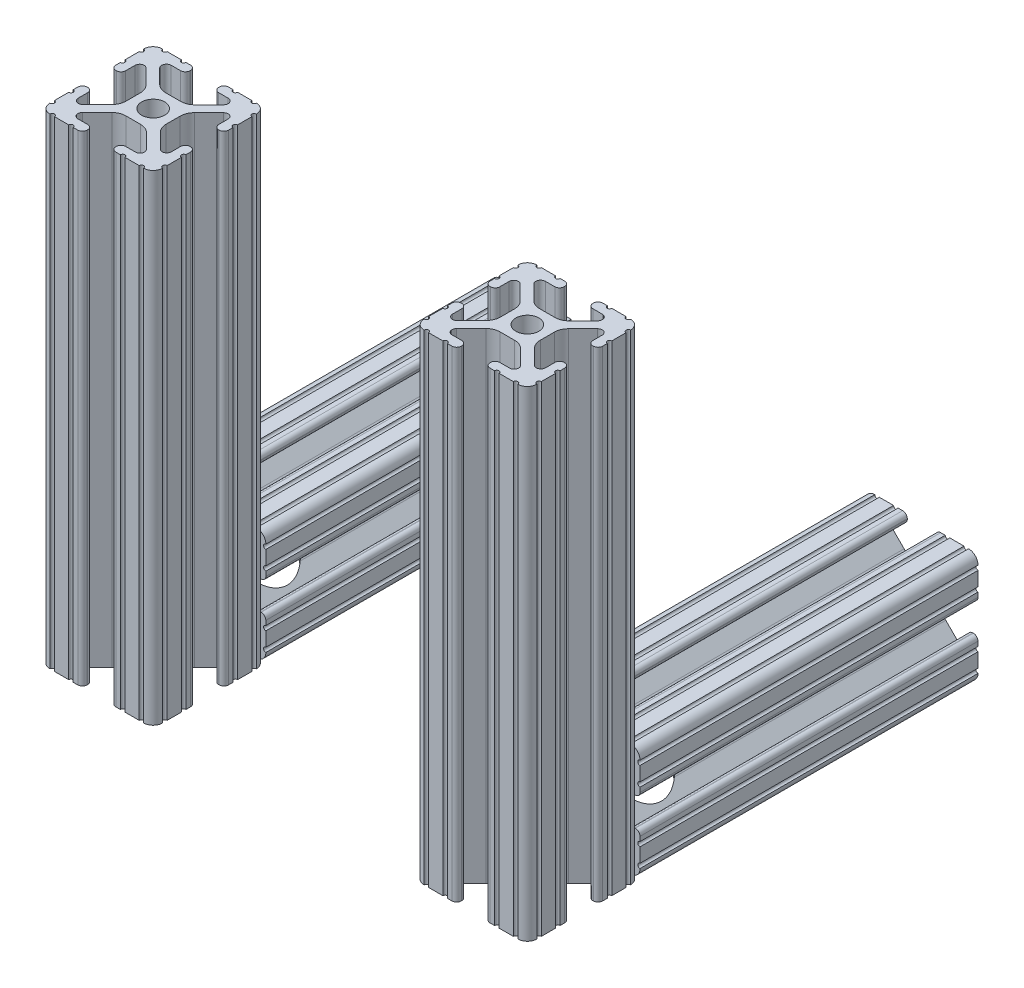
SolidWorks part; units mm, degrees
material "6061-T6 (SS)"
ref_plane "Front" through (0, 0, 0) normal (0, 0, 1) x (1, 0, 0)
ref_plane "Top" through (0, 0, 0) normal (0, 1, 0) x (1, 0, 0)
ref_plane "Right" through (0, 0, 0) normal (1, 0, 0) x (0, 0, -1)
sketch "Sketch1" plane through (0, 0, 0) normal (0, 0, 1) x (1, 0, 0)
  line L0 (0, -54.1622) -> (0, 54.1622)
  line L1 (42.1775, 54.1622) -> (42.1775, -54.1622)
  line L2 (-42.1775, 54.1622) -> (-42.1775, -54.1622)
  line L3 (-42.1775, 54.1622) -> (0, 54.1622) construction
  line L4 (0, 54.1622) -> (42.1775, 54.1622) construction
  line L5 (-42.1775, -54.1622) -> (0, -54.1622) construction
  line L6 (0, -54.1622) -> (42.1775, -54.1622) construction
  dimension "D1" = 108.3245
  dimension "D2" = 42.1775
other "10 1010 PROFILE(1)"
ref_plane "Plane1" through (-42.1775, 54.1622, 0) normal (0, -1, 0) x (1, 0, 0)
sketch "Sketch110" plane through (-42.1775, 54.1622, 0) normal (0, -1, 0) x (1, 0, 0)
  line L1 (12.7, 12.7) -> (-12.7, 12.7) construction
  line L2 (12.7, 12.7) -> (12.7, -12.7) construction
  line L3 (12.7, -12.7) -> (-12.7, -12.7) construction
  line L4 (-12.7, 12.7) -> (-12.7, -12.7) construction
  line L5 (12.7, 12.7) -> (-12.7, -12.7) construction
  line L6 (12.7, -12.7) -> (-12.7, 12.7) construction
  line L88 (-1.7093, -4.4958) -> (1.7093, -4.4958)
  line L89 (3.9523, -5.4237) -> (7.1797, -8.6452)
  line L90 (6.4164, -10.4902) -> (4.2875, -10.4902)
  line L91 (3.2385, -11.5392) -> (3.2385, -11.651)
  line L92 (4.2875, -12.7) -> (5.3171, -12.7)
  line L93 (6.3331, -12.7) -> (9.5504, -12.7)
  line L94 (12.7, -9.5504) -> (12.7, -6.3331)
  line L95 (12.7, -5.3171) -> (12.7, -4.2875)
  line L96 (11.651, -3.2385) -> (11.5392, -3.2385)
  line L97 (10.4902, -4.2875) -> (10.4902, -6.4021)
  line L98 (8.737, -7.1292) -> (5.4405, -3.8388)
  line L99 (4.5085, -1.5917) -> (4.5085, 1.5917)
  line L100 (5.4405, 3.8388) -> (8.737, 7.1292)
  line L101 (10.4902, 6.4021) -> (10.4902, 4.2875)
  line L102 (11.5392, 3.2385) -> (11.651, 3.2385)
  line L103 (12.7, 4.2875) -> (12.7, 5.3171)
  line L104 (12.7, 6.3331) -> (12.7, 9.5504)
  line L105 (9.5504, 12.7) -> (6.3331, 12.7)
  line L106 (5.3171, 12.7) -> (4.2875, 12.7)
  line L107 (3.2384, 11.651) -> (3.2384, 11.5392)
  line L108 (4.2875, 10.4902) -> (6.4768, 10.4902)
  line L109 (7.2072, 8.7245) -> (3.9003, 5.4237)
  line L110 (1.6573, 4.4958) -> (-1.6573, 4.4958)
  line L111 (-3.9003, 5.4237) -> (-7.2072, 8.7245)
  line L112 (-6.4768, 10.4902) -> (-4.2875, 10.4902)
  line L113 (-3.2384, 11.5392) -> (-3.2384, 11.651)
  line L114 (-4.2875, 12.7) -> (-5.3171, 12.7)
  line L115 (-6.3331, 12.7) -> (-9.5504, 12.7)
  line L116 (-12.7, 9.5504) -> (-12.7, 6.3331)
  line L117 (-12.7, 5.3171) -> (-12.7, 4.2875)
  line L118 (-11.651, 3.2385) -> (-11.5392, 3.2385)
  line L119 (-10.4902, 4.2875) -> (-10.4902, 6.4021)
  line L120 (-8.737, 7.1292) -> (-5.4405, 3.8388)
  line L121 (-4.5085, 1.5917) -> (-4.5085, -1.5917)
  line L122 (-5.4405, -3.8388) -> (-8.737, -7.1292)
  line L123 (-10.4902, -6.4021) -> (-10.4902, -4.2875)
  line L124 (-11.5392, -3.2385) -> (-11.651, -3.2385)
  line L125 (-12.7, -4.2875) -> (-12.7, -5.3171)
  line L126 (-12.7, -6.3331) -> (-12.7, -9.5504)
  line L127 (-9.5504, -12.7) -> (-6.3331, -12.7)
  line L128 (-5.3171, -12.7) -> (-4.2875, -12.7)
  line L129 (-3.2385, -11.651) -> (-3.2385, -11.5392)
  line L130 (-4.2875, -10.4902) -> (-6.4164, -10.4902)
  line L131 (-7.1797, -8.6452) -> (-3.9523, -5.4237)
  circle A1 centre (0, 0) radius 2.6035
  arc A104 (-1.7093, -4.4958) -> (-3.9523, -5.4237) centre (-1.7093, -7.6708) ccw
  arc A105 (3.9523, -5.4237) -> (1.7093, -4.4958) centre (1.7093, -7.6708) ccw
  arc A106 (6.4164, -10.4902) -> (7.1797, -8.6452) centre (6.4164, -9.4098) ccw
  arc A107 (4.2875, -10.4902) -> (3.2385, -11.5392) centre (4.2875, -11.5392) ccw
  arc A108 (3.2385, -11.651) -> (4.2875, -12.7) centre (4.2875, -11.651) ccw
  arc A109 (6.3331, -12.7) -> (5.3171, -12.7) centre (5.8251, -12.7) ccw
  arc A110 (10.5664, -12.6998) -> (9.5504, -12.7) centre (10.0584, -12.7) ccw
  arc A111 (10.5664, -12.6998) -> (12.6998, -10.5664) centre (10.5918, -10.5918) ccw
  arc A112 (12.7, -9.5504) -> (12.6998, -10.5664) centre (12.7, -10.0584) ccw
  arc A113 (12.7, -5.3171) -> (12.7, -6.3331) centre (12.7, -5.8251) ccw
  arc A114 (12.7, -4.2875) -> (11.651, -3.2385) centre (11.651, -4.2875) ccw
  arc A115 (11.5392, -3.2385) -> (10.4902, -4.2875) centre (11.5392, -4.2875) ccw
  arc A116 (8.737, -7.1292) -> (10.4902, -6.4021) centre (9.4628, -6.4021) ccw
  arc A117 (4.5085, -1.5917) -> (5.4405, -3.8388) centre (7.6835, -1.5917) ccw
  arc A118 (5.4405, 3.8388) -> (4.5085, 1.5917) centre (7.6835, 1.5917) ccw
  arc A119 (10.4902, 6.4021) -> (8.737, 7.1292) centre (9.4628, 6.4021) ccw
  arc A120 (10.4902, 4.2875) -> (11.5392, 3.2385) centre (11.5392, 4.2875) ccw
  arc A121 (11.651, 3.2385) -> (12.7, 4.2875) centre (11.651, 4.2875) ccw
  arc A122 (12.7, 6.3331) -> (12.7, 5.3171) centre (12.7, 5.8251) ccw
  arc A123 (12.6998, 10.5664) -> (12.7, 9.5504) centre (12.7, 10.0584) ccw
  arc A124 (12.6998, 10.5664) -> (10.5664, 12.6998) centre (10.5918, 10.5918) ccw
  arc A125 (9.5504, 12.7) -> (10.5664, 12.6998) centre (10.0584, 12.7) ccw
  arc A126 (5.3171, 12.7) -> (6.3331, 12.7) centre (5.8251, 12.7) ccw
  arc A127 (4.2875, 12.7) -> (3.2384, 11.651) centre (4.2875, 11.651) ccw
  arc A128 (3.2384, 11.5392) -> (4.2875, 10.4902) centre (4.2875, 11.5392) ccw
  arc A129 (7.2072, 8.7245) -> (6.4768, 10.4902) centre (6.4768, 9.4563) ccw
  arc A130 (1.6573, 4.4958) -> (3.9003, 5.4237) centre (1.6573, 7.6708) ccw
  arc A131 (-3.9003, 5.4237) -> (-1.6573, 4.4958) centre (-1.6573, 7.6708) ccw
  arc A132 (-6.4768, 10.4902) -> (-7.2072, 8.7245) centre (-6.4768, 9.4563) ccw
  arc A133 (-4.2875, 10.4902) -> (-3.2384, 11.5392) centre (-4.2875, 11.5392) ccw
  arc A134 (-3.2384, 11.651) -> (-4.2875, 12.7) centre (-4.2875, 11.651) ccw
  arc A135 (-6.3331, 12.7) -> (-5.3171, 12.7) centre (-5.8251, 12.7) ccw
  arc A136 (-10.5664, 12.6998) -> (-9.5504, 12.7) centre (-10.0584, 12.7) ccw
  arc A137 (-10.5664, 12.6998) -> (-12.6998, 10.5664) centre (-10.5918, 10.5918) ccw
  arc A138 (-12.7, 9.5504) -> (-12.6998, 10.5664) centre (-12.7, 10.0584) ccw
  arc A139 (-12.7, 5.3171) -> (-12.7, 6.3331) centre (-12.7, 5.8251) ccw
  arc A140 (-12.7, 4.2875) -> (-11.651, 3.2385) centre (-11.651, 4.2875) ccw
  arc A141 (-11.5392, 3.2385) -> (-10.4902, 4.2875) centre (-11.5392, 4.2875) ccw
  arc A142 (-8.737, 7.1292) -> (-10.4902, 6.4021) centre (-9.4628, 6.4021) ccw
  arc A143 (-4.5085, 1.5917) -> (-5.4405, 3.8388) centre (-7.6835, 1.5917) ccw
  arc A144 (-5.4405, -3.8388) -> (-4.5085, -1.5917) centre (-7.6835, -1.5917) ccw
  arc A145 (-10.4902, -6.4021) -> (-8.737, -7.1292) centre (-9.4628, -6.4021) ccw
  arc A146 (-10.4902, -4.2875) -> (-11.5392, -3.2385) centre (-11.5392, -4.2875) ccw
  arc A147 (-11.651, -3.2385) -> (-12.7, -4.2875) centre (-11.651, -4.2875) ccw
  arc A148 (-12.7, -6.3331) -> (-12.7, -5.3171) centre (-12.7, -5.8251) ccw
  arc A149 (-12.6998, -10.5664) -> (-12.7, -9.5504) centre (-12.7, -10.0584) ccw
  arc A150 (-12.6998, -10.5664) -> (-10.5664, -12.6998) centre (-10.5918, -10.5918) ccw
  arc A151 (-9.5504, -12.7) -> (-10.5664, -12.6998) centre (-10.0584, -12.7) ccw
  arc A152 (-5.3171, -12.7) -> (-6.3331, -12.7) centre (-5.8251, -12.7) ccw
  arc A153 (-4.2875, -12.7) -> (-3.2385, -11.651) centre (-4.2875, -11.651) ccw
  arc A154 (-3.2385, -11.5392) -> (-4.2875, -10.4902) centre (-4.2875, -11.5392) ccw
  arc A155 (-7.1797, -8.6452) -> (-6.4164, -10.4902) centre (-6.4164, -9.4098) ccw
  point P3 (0, 0)
  point P21 (-12.7, 0)
  point P22 (0, 12.7)
  point P25 (12.7, 0)
  point P28 (0, -12.7)
  point P30 (-12.7, -12.7)
  point P33 (12.7, -12.7)
  point P37 (12.7, 12.7)
  point P40 (-12.7, 12.7)
  point P43 (0, 0)
  dimension "D1" = 25.4
ref_plane "Plane2" through (0, -41.4622, 0) normal (0, -1, 0) x (-1, 0, 0)
sketch "Sketch111" plane through (0, -41.4622, 0) normal (0, -1, 0) x (1, 0, 0)
  line L0 (42.1775, -12.7) -> (42.1775, -88.9)
  line L1 (-42.1775, -12.7) -> (-42.1775, -88.9)
  line L2 (-35.8444, -12.7) -> (-32.6271, -12.7) construction
  line L3 (-46.465, -12.7) -> (-42.1775, -12.7) construction
  line L4 (-42.1775, -12.7) -> (-37.89, -12.7) construction
  line L5 (47.4946, -12.7) -> (42.1775, -12.7) construction
  line L6 (42.1775, -12.7) -> (36.8604, -12.7) construction
  dimension "D1" = 76.2
other "10 1010 PROFILE(3)"
ref_plane "Plane3" through (42.1775, -41.4622, -12.7) normal (0, 0, -1) x (1, 0, 0)
sketch "Sketch113" plane through (42.1775, -41.4622, -12.7) normal (0, 0, -1) x (1, 0, 0)
  line L1 (12.7, 12.7) -> (-12.7, 12.7) construction
  line L2 (12.7, 12.7) -> (12.7, -12.7) construction
  line L3 (12.7, -12.7) -> (-12.7, -12.7) construction
  line L4 (-12.7, 12.7) -> (-12.7, -12.7) construction
  line L5 (12.7, 12.7) -> (-12.7, -12.7) construction
  line L6 (12.7, -12.7) -> (-12.7, 12.7) construction
  line L88 (-1.7093, -4.4958) -> (1.7093, -4.4958)
  line L89 (3.9523, -5.4237) -> (7.1797, -8.6452)
  line L90 (6.4164, -10.4902) -> (4.2875, -10.4902)
  line L91 (3.2385, -11.5392) -> (3.2385, -11.651)
  line L92 (4.2875, -12.7) -> (5.3171, -12.7)
  line L93 (6.3331, -12.7) -> (9.5504, -12.7)
  line L94 (12.7, -9.5504) -> (12.7, -6.3331)
  line L95 (12.7, -5.3171) -> (12.7, -4.2875)
  line L96 (11.651, -3.2385) -> (11.5392, -3.2385)
  line L97 (10.4902, -4.2875) -> (10.4902, -6.4021)
  line L98 (8.737, -7.1292) -> (5.4405, -3.8388)
  line L99 (4.5085, -1.5917) -> (4.5085, 1.5917)
  line L100 (5.4405, 3.8388) -> (8.737, 7.1292)
  line L101 (10.4902, 6.4021) -> (10.4902, 4.2875)
  line L102 (11.5392, 3.2385) -> (11.651, 3.2385)
  line L103 (12.7, 4.2875) -> (12.7, 5.3171)
  line L104 (12.7, 6.3331) -> (12.7, 9.5504)
  line L105 (9.5504, 12.7) -> (6.3331, 12.7)
  line L106 (5.3171, 12.7) -> (4.2875, 12.7)
  line L107 (3.2384, 11.651) -> (3.2384, 11.5392)
  line L108 (4.2875, 10.4902) -> (6.4768, 10.4902)
  line L109 (7.2072, 8.7245) -> (3.9003, 5.4237)
  line L110 (1.6573, 4.4958) -> (-1.6573, 4.4958)
  line L111 (-3.9003, 5.4237) -> (-7.2072, 8.7245)
  line L112 (-6.4768, 10.4902) -> (-4.2875, 10.4902)
  line L113 (-3.2384, 11.5392) -> (-3.2384, 11.651)
  line L114 (-4.2875, 12.7) -> (-5.3171, 12.7)
  line L115 (-6.3331, 12.7) -> (-9.5504, 12.7)
  line L116 (-12.7, 9.5504) -> (-12.7, 6.3331)
  line L117 (-12.7, 5.3171) -> (-12.7, 4.2875)
  line L118 (-11.651, 3.2385) -> (-11.5392, 3.2385)
  line L119 (-10.4902, 4.2875) -> (-10.4902, 6.4021)
  line L120 (-8.737, 7.1292) -> (-5.4405, 3.8388)
  line L121 (-4.5085, 1.5917) -> (-4.5085, -1.5917)
  line L122 (-5.4405, -3.8388) -> (-8.737, -7.1292)
  line L123 (-10.4902, -6.4021) -> (-10.4902, -4.2875)
  line L124 (-11.5392, -3.2385) -> (-11.651, -3.2385)
  line L125 (-12.7, -4.2875) -> (-12.7, -5.3171)
  line L126 (-12.7, -6.3331) -> (-12.7, -9.5504)
  line L127 (-9.5504, -12.7) -> (-6.3331, -12.7)
  line L128 (-5.3171, -12.7) -> (-4.2875, -12.7)
  line L129 (-3.2385, -11.651) -> (-3.2385, -11.5392)
  line L130 (-4.2875, -10.4902) -> (-6.4164, -10.4902)
  line L131 (-7.1797, -8.6452) -> (-3.9523, -5.4237)
  circle A1 centre (0, 0) radius 2.6035
  arc A104 (-1.7093, -4.4958) -> (-3.9523, -5.4237) centre (-1.7093, -7.6708) ccw
  arc A105 (3.9523, -5.4237) -> (1.7093, -4.4958) centre (1.7093, -7.6708) ccw
  arc A106 (6.4164, -10.4902) -> (7.1797, -8.6452) centre (6.4164, -9.4098) ccw
  arc A107 (4.2875, -10.4902) -> (3.2385, -11.5392) centre (4.2875, -11.5392) ccw
  arc A108 (3.2385, -11.651) -> (4.2875, -12.7) centre (4.2875, -11.651) ccw
  arc A109 (6.3331, -12.7) -> (5.3171, -12.7) centre (5.8251, -12.7) ccw
  arc A110 (10.5664, -12.6998) -> (9.5504, -12.7) centre (10.0584, -12.7) ccw
  arc A111 (10.5664, -12.6998) -> (12.6998, -10.5664) centre (10.5918, -10.5918) ccw
  arc A112 (12.7, -9.5504) -> (12.6998, -10.5664) centre (12.7, -10.0584) ccw
  arc A113 (12.7, -5.3171) -> (12.7, -6.3331) centre (12.7, -5.8251) ccw
  arc A114 (12.7, -4.2875) -> (11.651, -3.2385) centre (11.651, -4.2875) ccw
  arc A115 (11.5392, -3.2385) -> (10.4902, -4.2875) centre (11.5392, -4.2875) ccw
  arc A116 (8.737, -7.1292) -> (10.4902, -6.4021) centre (9.4628, -6.4021) ccw
  arc A117 (4.5085, -1.5917) -> (5.4405, -3.8388) centre (7.6835, -1.5917) ccw
  arc A118 (5.4405, 3.8388) -> (4.5085, 1.5917) centre (7.6835, 1.5917) ccw
  arc A119 (10.4902, 6.4021) -> (8.737, 7.1292) centre (9.4628, 6.4021) ccw
  arc A120 (10.4902, 4.2875) -> (11.5392, 3.2385) centre (11.5392, 4.2875) ccw
  arc A121 (11.651, 3.2385) -> (12.7, 4.2875) centre (11.651, 4.2875) ccw
  arc A122 (12.7, 6.3331) -> (12.7, 5.3171) centre (12.7, 5.8251) ccw
  arc A123 (12.6998, 10.5664) -> (12.7, 9.5504) centre (12.7, 10.0584) ccw
  arc A124 (12.6998, 10.5664) -> (10.5664, 12.6998) centre (10.5918, 10.5918) ccw
  arc A125 (9.5504, 12.7) -> (10.5664, 12.6998) centre (10.0584, 12.7) ccw
  arc A126 (5.3171, 12.7) -> (6.3331, 12.7) centre (5.8251, 12.7) ccw
  arc A127 (4.2875, 12.7) -> (3.2384, 11.651) centre (4.2875, 11.651) ccw
  arc A128 (3.2384, 11.5392) -> (4.2875, 10.4902) centre (4.2875, 11.5392) ccw
  arc A129 (7.2072, 8.7245) -> (6.4768, 10.4902) centre (6.4768, 9.4563) ccw
  arc A130 (1.6573, 4.4958) -> (3.9003, 5.4237) centre (1.6573, 7.6708) ccw
  arc A131 (-3.9003, 5.4237) -> (-1.6573, 4.4958) centre (-1.6573, 7.6708) ccw
  arc A132 (-6.4768, 10.4902) -> (-7.2072, 8.7245) centre (-6.4768, 9.4563) ccw
  arc A133 (-4.2875, 10.4902) -> (-3.2384, 11.5392) centre (-4.2875, 11.5392) ccw
  arc A134 (-3.2384, 11.651) -> (-4.2875, 12.7) centre (-4.2875, 11.651) ccw
  arc A135 (-6.3331, 12.7) -> (-5.3171, 12.7) centre (-5.8251, 12.7) ccw
  arc A136 (-10.5664, 12.6998) -> (-9.5504, 12.7) centre (-10.0584, 12.7) ccw
  arc A137 (-10.5664, 12.6998) -> (-12.6998, 10.5664) centre (-10.5918, 10.5918) ccw
  arc A138 (-12.7, 9.5504) -> (-12.6998, 10.5664) centre (-12.7, 10.0584) ccw
  arc A139 (-12.7, 5.3171) -> (-12.7, 6.3331) centre (-12.7, 5.8251) ccw
  arc A140 (-12.7, 4.2875) -> (-11.651, 3.2385) centre (-11.651, 4.2875) ccw
  arc A141 (-11.5392, 3.2385) -> (-10.4902, 4.2875) centre (-11.5392, 4.2875) ccw
  arc A142 (-8.737, 7.1292) -> (-10.4902, 6.4021) centre (-9.4628, 6.4021) ccw
  arc A143 (-4.5085, 1.5917) -> (-5.4405, 3.8388) centre (-7.6835, 1.5917) ccw
  arc A144 (-5.4405, -3.8388) -> (-4.5085, -1.5917) centre (-7.6835, -1.5917) ccw
  arc A145 (-10.4902, -6.4021) -> (-8.737, -7.1292) centre (-9.4628, -6.4021) ccw
  arc A146 (-10.4902, -4.2875) -> (-11.5392, -3.2385) centre (-11.5392, -4.2875) ccw
  arc A147 (-11.651, -3.2385) -> (-12.7, -4.2875) centre (-11.651, -4.2875) ccw
  arc A148 (-12.7, -6.3331) -> (-12.7, -5.3171) centre (-12.7, -5.8251) ccw
  arc A149 (-12.6998, -10.5664) -> (-12.7, -9.5504) centre (-12.7, -10.0584) ccw
  arc A150 (-12.6998, -10.5664) -> (-10.5664, -12.6998) centre (-10.5918, -10.5918) ccw
  arc A151 (-9.5504, -12.7) -> (-10.5664, -12.6998) centre (-10.0584, -12.7) ccw
  arc A152 (-5.3171, -12.7) -> (-6.3331, -12.7) centre (-5.8251, -12.7) ccw
  arc A153 (-4.2875, -12.7) -> (-3.2385, -11.651) centre (-4.2875, -11.651) ccw
  arc A154 (-3.2385, -11.5392) -> (-4.2875, -10.4902) centre (-4.2875, -11.5392) ccw
  arc A155 (-7.1797, -8.6452) -> (-6.4164, -10.4902) centre (-6.4164, -9.4098) ccw
  point P3 (0, 0)
  point P21 (-12.7, 0)
  point P22 (0, 12.7)
  point P25 (12.7, 0)
  point P28 (0, -12.7)
  point P30 (-12.7, -12.7)
  point P33 (12.7, -12.7)
  point P37 (12.7, 12.7)
  point P40 (-12.7, 12.7)
  point P43 (0, 0)
  dimension "D1" = 25.4
sketch "Sketch114" plane through (0, -54.1622, 0) normal (0, -1, 0) x (1, 0, 0)
  line L0 (37.89, -12.7) -> (42.1775, -23.2) construction
  line L1 (42.1775, -23.2) -> (46.465, -12.7) construction
  line L2 (48.5106, -12.7) -> (51.7279, -12.7) construction
  circle A0 centre (42.1775, -23.2) radius 7.065
  dimension "D2" = 14.13
  dimension "D1" = 10.5
extrude "Cut-Extrude1" cut sketch "Sketch114" against normal blind 10.414
sketch "Sketch115" plane through (0, -54.1622, 0) normal (0, -1, 0) x (1, 0, 0)
  line L0 (-46.465, -12.7) -> (-42.1775, -23.2) construction
  line L1 (-42.1775, -23.2) -> (-37.89, -12.7) construction
  line L2 (-35.8444, -12.7) -> (-32.6271, -12.7) construction
  circle A0 centre (-42.1775, -23.2) radius 7.065
  dimension "D2" = 14.13
  dimension "D1" = 10.5
extrude "Cut-Extrude2" cut sketch "Sketch115" against normal blind 10.414
